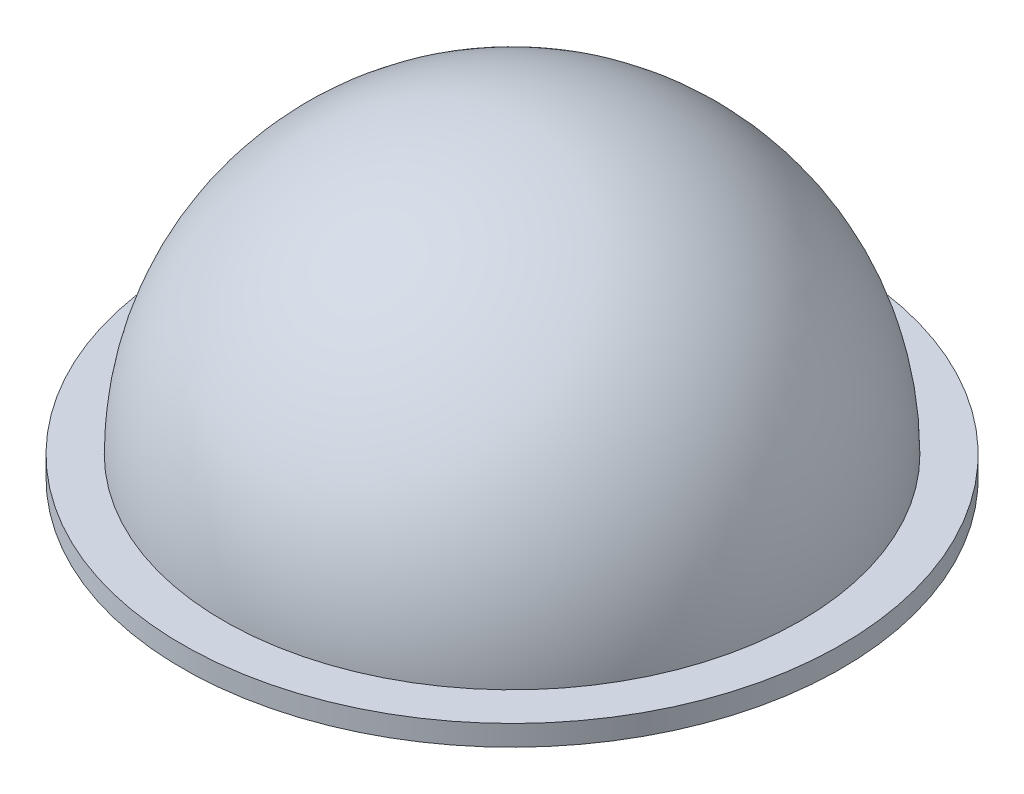
SolidWorks part; units mm, degrees
material "Acrylic (Medium-high impact)"
ref_plane "Front" through (0, 0, 0) normal (0, 0, 1) x (1, 0, 0)
ref_plane "Top" through (0, 0, 0) normal (0, 1, 0) x (1, 0, 0)
ref_plane "Right" through (0, 0, 0) normal (1, 0, 0) x (0, 0, -1)
sketch "Sketch1" plane through (0, 0, 0) normal (0, 0, 1) x (1, 0, 0)
  line L0 (0, 0) -> (0, 95.25) construction
  line L1 (85.55, 0) -> (101.6, 0)
  line L2 (101.6, 0) -> (101.6, 6.35)
  line L3 (101.6, 6.35) -> (88.9, 6.35)
  line L4 (82.55, 6.35) -> (82.55, 3)
  line L5 (0, 95.25) -> (0, 88.9)
  line L6 (82.55, 3) -> (85.55, 0)
  arc A0 (88.9, 6.35) -> (0, 95.25) centre (0, 6.35) ccw
  arc A1 (82.55, 6.35) -> (0, 88.9) centre (0, 6.35) ccw
  arc A2 (82.55, 6.35) -> (2.5896, 88.8594) centre (0, 6.35) ccw construction
  arc A3 (88.9, 6.35) -> (2.7888, 95.2062) centre (0, 6.35) ccw construction
  point P3 (82.55, 0)
  dimension "D1" = 6.35
  dimension "D2" = 6.35
  dimension "D3" = 88.9
  dimension "D4" = 12.7
revolve "Revolve1" add sketch "Sketch1" angle 360 about L0
